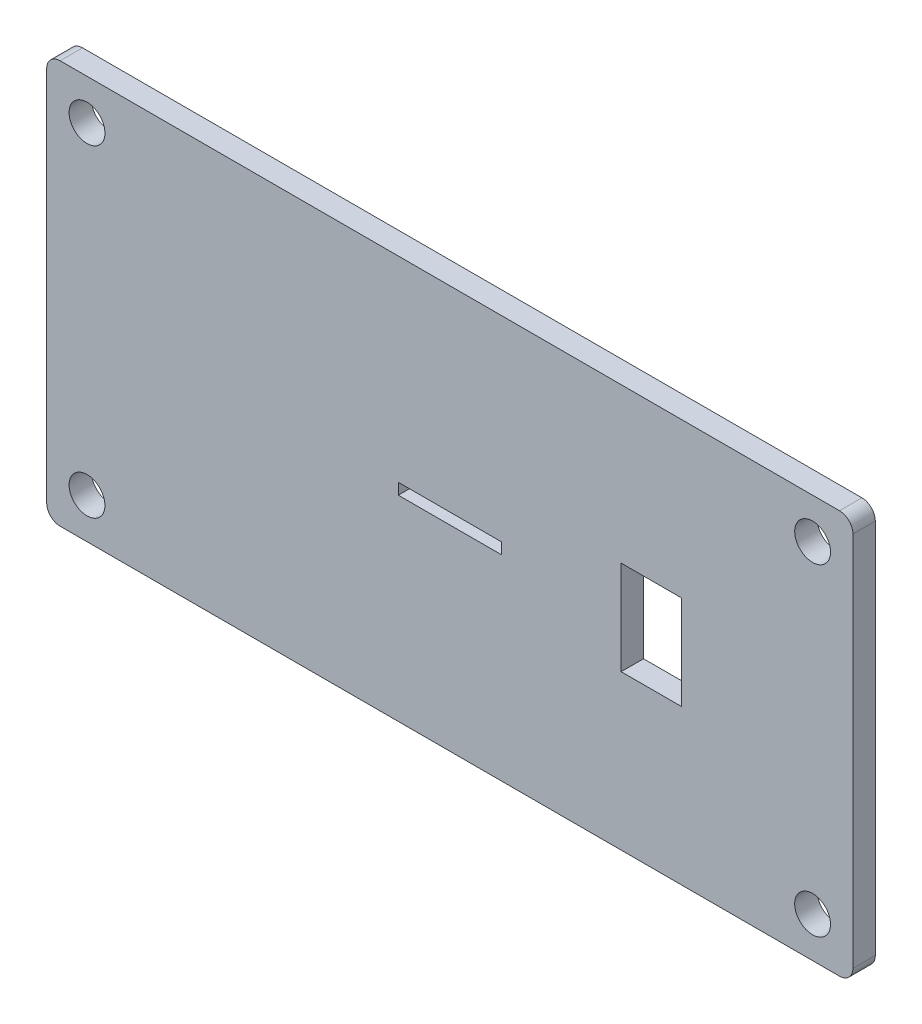
SolidWorks part; units mm, degrees
ref_plane "Front Plane" through (0, 0, 0) normal (0, 0, 1) x (1, 0, 0)
ref_plane "Top Plane" through (0, 0, 0) normal (0, 1, 0) x (1, 0, 0)
ref_plane "Right Plane" through (0, 0, 0) normal (1, 0, 0) x (0, 0, -1)
sketch "Sketch1" plane through (0, 0, 0) normal (0, 0, 1) x (1, 0, 0)
  line L1 (-90, 45) -> (90, 45)
  line L2 (-90, 45) -> (-90, -45)
  line L3 (-90, -45) -> (90, -45)
  line L4 (90, 45) -> (90, -45)
  line L5 (-90, 45) -> (90, -45) construction
  line L6 (-90, -45) -> (90, 45) construction
  point P0 (0, 0)
  dimension "D1" = 180
  dimension "D2" = 90
extrude "Boss-Extrude1" add sketch "Sketch1" along normal blind 5
sketch "Sketch2" plane through (0, 0, 5) normal (0, 0, 1) x (1, 0, 0)
  line L0 (90, 45) -> (-90, 45) construction
  line L1 (-90, 45) -> (-90, -45) construction
  line L2 (0, 36) -> (0, -24.0238) construction
  line L3 (-62.0492, 0) -> (66.1759, 0) construction
  circle A0 centre (-81, 36) radius 4
  circle A1 centre (81, 36) radius 4
  circle A2 centre (81, -36) radius 4
  circle A3 centre (-81, -36) radius 4
  dimension "D1" = 8
  dimension "D2" = 9
  dimension "D3" = 9
extrude "Cut-Extrude1" cut sketch "Sketch2" against normal through all
sketch "Sketch3" plane through (0, 0, 0) normal (0, 0, -1) x (-1, 0, 0)
  line L1 (-11.5, -1.25) -> (11.5, -1.25)
  line L2 (-11.5, -1.25) -> (-11.5, 1.25)
  line L3 (-11.5, 1.25) -> (11.5, 1.25)
  line L4 (11.5, -1.25) -> (11.5, 1.25)
  line L5 (-11.5, -1.25) -> (11.5, 1.25) construction
  line L6 (-11.5, 1.25) -> (11.5, -1.25) construction
  point P0 (0, 0)
  dimension "D1" = 2.5
  dimension "D2" = 23
extrude "Cut-Extrude2" cut sketch "Sketch3" against normal through all
fillet "Fillet1" radius 3 1 edges at (90, 45, 2.5)
fillet "Fillet2" radius 3 1 edges at (90, -45, 2.5)
fillet "Fillet3" radius 3 1 edges at (-90, 45, 2.5)
fillet "Fillet4" radius 3 1 edges at (-90, -45, 2.5)
sketch "Sketch4" plane through (0, 0, 5) normal (0, 0, 1) x (1, 0, 0)
  line L0 (-87, -45) -> (87, -45) construction
  line L1 (51.75, -10.5) -> (38.25, -10.5)
  line L2 (51.75, -10.5) -> (51.75, 10.5)
  line L3 (51.75, 10.5) -> (38.25, 10.5)
  line L4 (38.25, -10.5) -> (38.25, 10.5)
  line L5 (51.75, -10.5) -> (38.25, 10.5) construction
  line L6 (51.75, 10.5) -> (38.25, -10.5) construction
  line L8 (90, -42) -> (90, 42) construction
  point P0 (45, 0)
  point P7 (51.75, 0)
  dimension "D1" = 13.5
  dimension "D2" = 21
  dimension "D3" = 34.5
  dimension "D4" = 38.25
extrude "Cut-Extrude3" cut sketch "Sketch4" against normal through all
